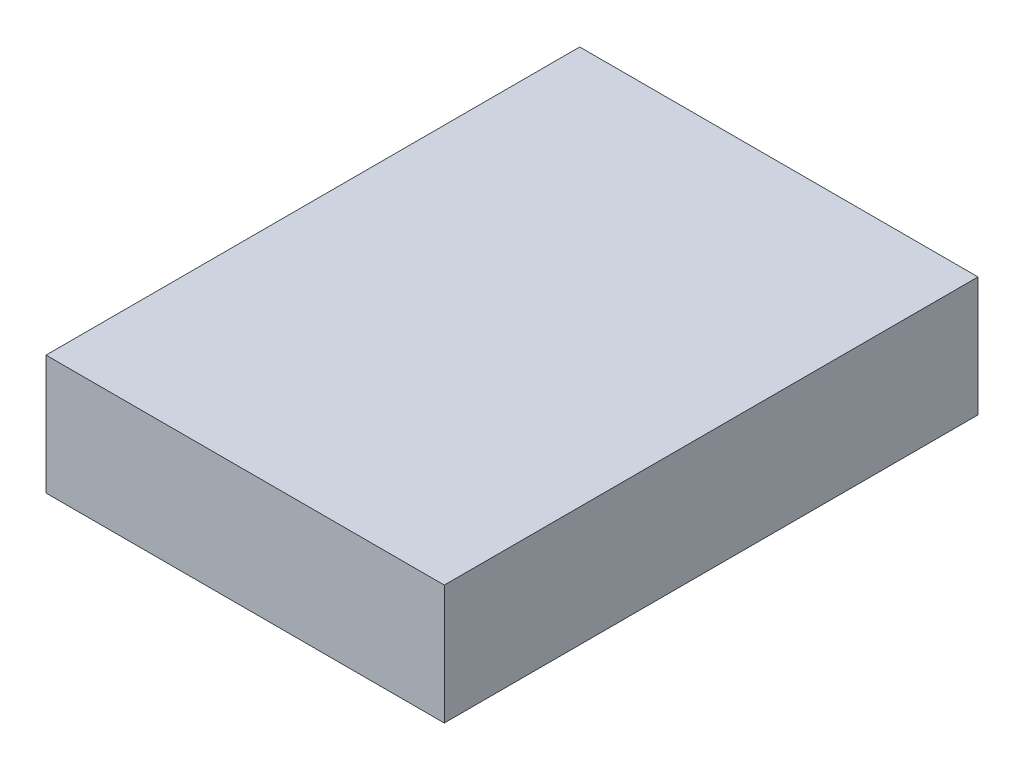
SolidWorks part; units mm, degrees
ref_plane "Front Plane" through (0, 0, 0) normal (0, 0, 1) x (1, 0, 0)
ref_plane "Top Plane" through (0, 0, 0) normal (0, 1, 0) x (1, 0, 0)
ref_plane "Right Plane" through (0, 0, 0) normal (1, 0, 0) x (0, 0, -1)
sketch "Sketch1" plane through (0, 0, 0) normal (0, 1, 0) x (1, 0, 0)
  line L5 (-25, 33.5) -> (25, 33.5)
  line L6 (-25, 33.5) -> (-25, -33.5)
  line L7 (-25, -33.5) -> (25, -33.5)
  line L8 (25, 33.5) -> (25, -33.5)
  point P5 (0, 33.5)
  point P7 (-25, 0)
  dimension "D1" = 50
  dimension "D2" = 67
extrude "Boss-Extrude1" add sketch "Sketch1" along normal blind 15
